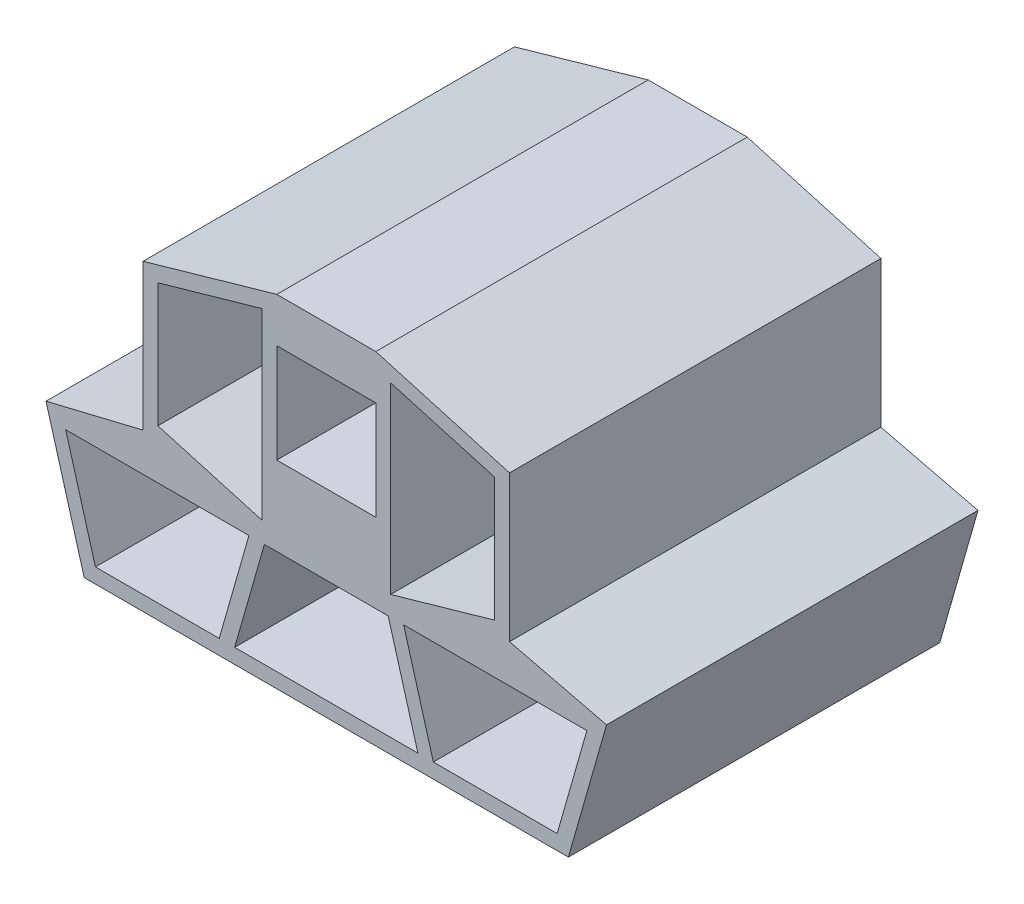
SolidWorks part; units mm, degrees
ref_plane "Front Plane" through (0, 0, 0) normal (0, 0, 1) x (1, 0, 0)
ref_plane "Top Plane" through (0, 0, 0) normal (0, 1, 0) x (1, 0, 0)
ref_plane "Right Plane" through (0, 0, 0) normal (1, 0, 0) x (0, 0, -1)
sketch "Sketch1" plane through (0, 0, 0) normal (0, 0, 1) x (1, 0, 0)
  line L0 (0, 45.5072) -> (0, -40.4348) construction
  line L1 (-48.8406, 0) -> (45.7971, 0) construction
  line L3 (10, -10) -> (-10, -10)
  line L4 (10, -10) -> (10, 10)
  line L5 (10, 10) -> (-10, 10)
  line L6 (-10, -10) -> (-10, 10)
  line L7 (10, -10) -> (-10, 10) construction
  line L8 (10, 10) -> (-10, -10) construction
  line L18 (-12.5, -26) -> (12.5, -26)
  line L19 (12.5, -26) -> (18.5, -47)
  line L20 (-18.5, -47) -> (18.5, -47)
  line L21 (-12.5, -26) -> (-18.5, -47)
  line L40 (15.62, -26) -> (21.62, -47)
  line L45 (15.62, -26) -> (52.62, -26)
  line L47 (52.62, -26) -> (46.62, -47)
  line L49 (46.62, -47) -> (21.62, -47)
  line L51 (56.5972, -23) -> (48.883, -50)
  line L54 (15.62, -23) -> (56.5972, -23) construction
  line L55 (-15.62, -26) -> (-52.62, -26)
  line L56 (14.7629, -23) -> (22.4772, -50) construction
  line L57 (-22.4772, -50) -> (22.4772, -50) construction
  line L58 (48.883, -50) -> (21.62, -50) construction
  line L59 (-52.62, -26) -> (-46.62, -47)
  line L60 (-46.62, -47) -> (-21.62, -47)
  line L61 (-15.62, -26) -> (-21.62, -47)
  line L62 (-14.7629, -23) -> (-22.4772, -50) construction
  line L64 (-56.5972, -23) -> (-48.883, -50)
  line L67 (-11.6429, -23) -> (-19.3571, -50) construction
  line L68 (-11.6429, -23) -> (-56.5972, -23) construction
  line L69 (-14.7629, -23) -> (14.7629, -23) construction
  line L70 (-48.883, -50) -> (-19.3571, -50) construction
  line L71 (-48.883, -50) -> (48.883, -50)
  line L72 (-13, -22) -> (-13, 15)
  line L73 (-13, 15) -> (-34, 9)
  line L74 (-34, 9) -> (-34, -16)
  line L75 (-34, -16) -> (-13, -22)
  line L76 (-39.4516, -3.5) -> (45.7971, -3.5) construction
  line L77 (34, 9) -> (34, -16)
  line L78 (13, 15) -> (34, 9)
  line L79 (13, -22) -> (13, 15)
  line L80 (34, -16) -> (13, -22)
  line L83 (-10, 18.9772) -> (-37, 11.2629)
  line L84 (-37, 11.2629) -> (-37, -18.2629)
  line L85 (-10, -25.9772) -> (-10, 18.9772) construction
  line L86 (-37, -18.2629) -> (-10, -25.9772) construction
  line L87 (-56.5972, -23) -> (-37, -18.2629)
  line L88 (-10, 18.9772) -> (0, 18.9772)
  line L89 (37, 11.2629) -> (37, -18.2629)
  line L92 (10, 18.9772) -> (37, 11.2629)
  line L93 (10, -25.9772) -> (10, 18.9772) construction
  line L94 (37, -18.2629) -> (10, -25.9772) construction
  line L95 (56.5972, -23) -> (37, -18.2629)
  line L96 (10, 18.9772) -> (0, 18.9772)
  point P5 (0, 0)
  point P10 (0, 0)
  point P13 (0, 14)
  point P14 (0, 35)
  point P16 (22.4772, 38)
  point P18 (-22.4772, 38)
  point P19 (0, 35)
  point P20 (-14.7629, 11)
  point P33 (14.7629, 11)
  dimension "D1" = 20
  dimension "D2" = 20
  dimension "D3" = 25
  dimension "D4" = 37
  dimension "D5" = 21
  dimension "D6" = 3
  dimension "D8" = 16
  dimension "D9" = 18.5
  dimension "D10" = 3
  dimension "D11" = 37
  dimension "D7" = 12.5
  dimension "D13" = 3
  dimension "D14" = 37
  dimension "D15" = 25
  dimension "D16" = 3.5
  dimension "D17" = 12.5
  dimension "D18" = 18.5
  dimension "D19" = 21
  dimension "D12" = 3
  dimension "D20" = 3
  dimension "D21" = 3
extrude "Boss-Extrude1" add sketch "Sketch1" along normal blind 75
